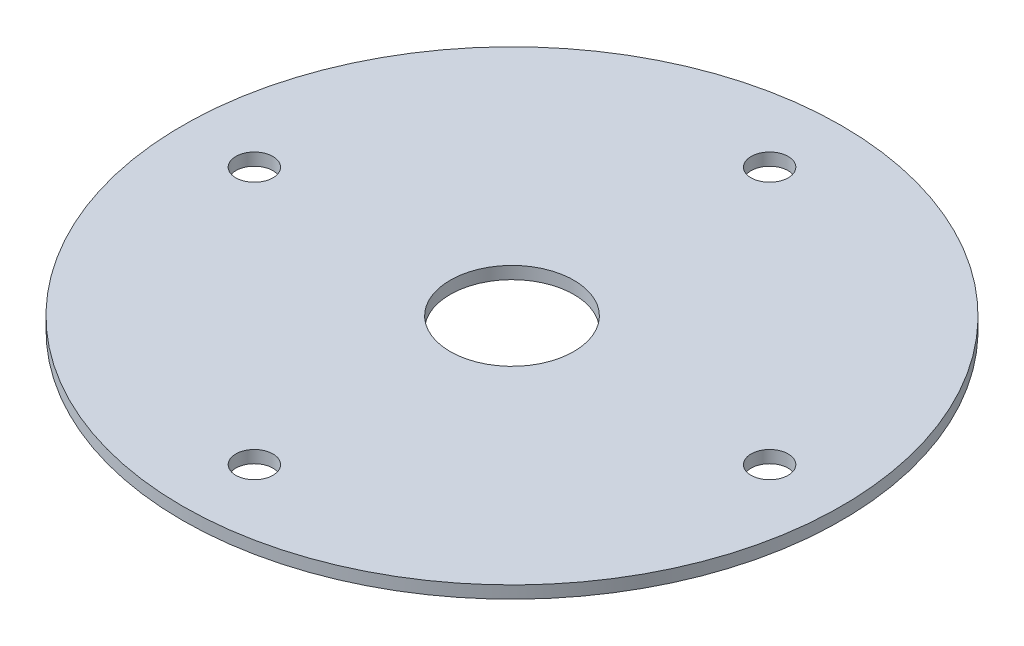
SolidWorks part; units mm, degrees
ref_plane "Front Plane" through (0, 0, 0) normal (0, 0, 1) x (1, 0, 0)
ref_plane "Top Plane" through (0, 0, 0) normal (0, 1, 0) x (1, 0, 0)
ref_plane "Right Plane" through (0, 0, 0) normal (1, 0, 0) x (0, 0, -1)
sketch "Sketch1" plane through (0, 0, 0) normal (0, 1, 0) x (1, 0, 0)
  circle A0 centre (0, 0) radius 79.95
  circle A1 centre (0, 0) radius 15
  circle A2 centre (0, 0) radius 62.5 construction
  circle A3 centre (0, 62.5) radius 4.5
  circle A4 centre (62.5, 0) radius 4.5
  circle A5 centre (0, -62.5) radius 4.5
  circle A6 centre (-62.5, 0) radius 4.5
  point P16 (0, 0)
  dimension "D1" = 159.9
  dimension "D2" = 30
  dimension "D3" = 125
  dimension "D4" = 9
  dimension "D5" = 4
extrude "Boss-Extrude1" add sketch "Sketch1" along normal blind 3
